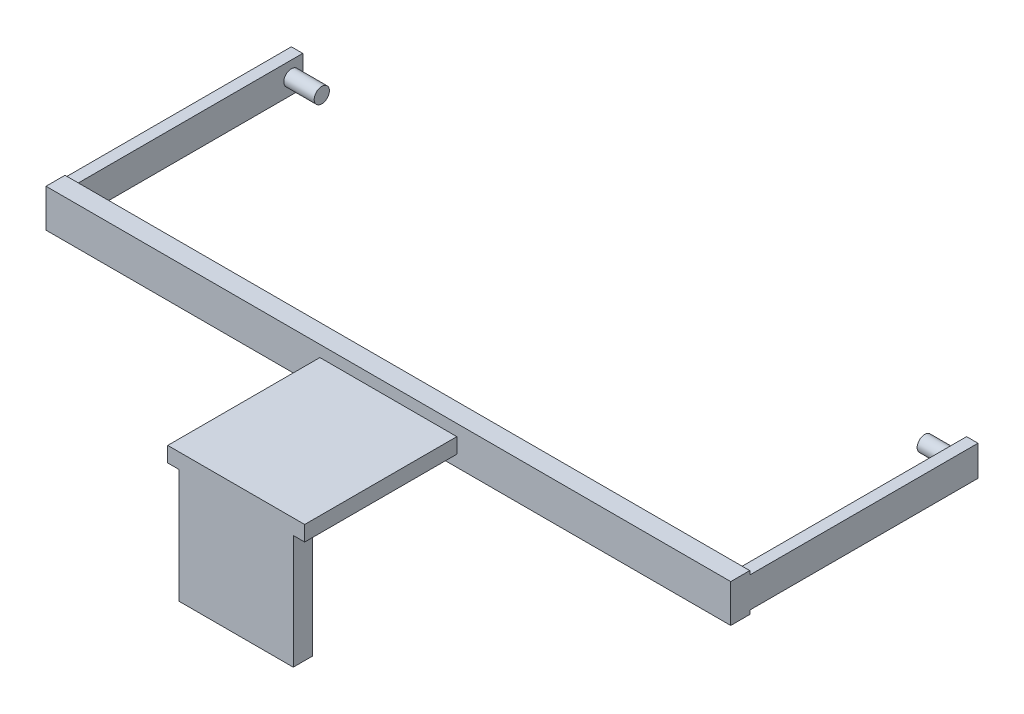
SolidWorks part; units mm, degrees
ref_plane "前视基准面" through (0, 0, 0) normal (0, 0, 1) x (1, 0, 0)
ref_plane "上视基准面" through (0, 0, 0) normal (0, 1, 0) x (1, 0, 0)
ref_plane "右视基准面" through (0, 0, 0) normal (1, 0, 0) x (0, 0, -1)
sketch "草图1" plane through (0, 0, 0) normal (0, 1, 0) x (1, 0, 0)
  line L1 (-90, 2.5) -> (90, 2.5)
  line L2 (-90, 2.5) -> (-90, -2.5)
  line L3 (-90, -2.5) -> (90, -2.5)
  line L4 (90, 2.5) -> (90, -2.5)
  line L5 (-90, 2.5) -> (90, -2.5) construction
  line L6 (-90, -2.5) -> (90, 2.5) construction
  point P0 (0, 0)
  dimension "D1" = 90
  dimension "D2" = 5
extrude "凸台-拉伸1" add sketch "草图1" along normal blind 10
sketch "草图2" plane through (0, 0, -2.5) normal (0, 0, -1) x (-1, 0, 0)
  line L0 (-90, 10) -> (-90, 0) construction
  line L1 (-90, 1) -> (-87, 1)
  line L2 (-90, 1) -> (-90, 9)
  line L3 (-90, 9) -> (-87, 9)
  line L4 (-87, 1) -> (-87, 9)
  line L5 (-90, 1) -> (-87, 9) construction
  line L6 (-90, 9) -> (-87, 1) construction
  line L7 (90, 10) -> (-90, 10) construction
  point P0 (-88.5, 5)
  point P7 (-88.5, 9)
  dimension "D1" = 3
  dimension "D2" = 0
  dimension "D3" = 8
  dimension "D4" = 1
extrude "凸台-拉伸2" add sketch "草图2" along normal blind 60
sketch "草图5" plane through (87, 0, 0) normal (-1, 0, 0) x (0, 0, 1)
  line L0 (-62.5, 9) -> (-2.5, 9) construction
  line L1 (-62.5, 1) -> (-62.5, 9) construction
  circle A0 centre (-59.5, 5) radius 2
  dimension "D1" = 4
  dimension "D2" = 4
  dimension "D3" = 3
extrude "凸台-拉伸4" add sketch "草图5" along normal blind 8
sketch "草图6" plane through (0, 0, 2.5) normal (0, 0, 1) x (1, 0, 0)
  line L0 (-90, 0) -> (90, 0) construction
  line L1 (-18, 7) -> (18, 7)
  line L2 (-18, 7) -> (-18, 3)
  line L3 (-18, 3) -> (18, 3)
  line L4 (18, 7) -> (18, 3)
  line L5 (-18, 7) -> (18, 3) construction
  line L6 (-18, 3) -> (18, 7) construction
  line L7 (90, 10) -> (90, 0) construction
  point P0 (0, 5)
  dimension "D1" = 5
  dimension "D2" = 90
  dimension "D3" = 4
  dimension "D4" = 36
extrude "凸台-拉伸5" add sketch "草图6" along normal blind 40
sketch "草图7" plane through (0, 3, 0) normal (0, -1, 0) x (1, 0, 0)
  line L0 (-18, 42.5) -> (18, 42.5) construction
  line L1 (15, 37.5) -> (-15, 37.5)
  line L2 (15, 37.5) -> (15, 42.5)
  line L3 (15, 42.5) -> (-15, 42.5)
  line L4 (-15, 37.5) -> (-15, 42.5)
  line L5 (15, 37.5) -> (-15, 42.5) construction
  line L6 (15, 42.5) -> (-15, 37.5) construction
  point P0 (0, 40)
  dimension "D1" = 5
  dimension "D2" = 30
extrude "凸台-拉伸6" add sketch "草图7" along normal blind 30
pattern_linear "阵列(线性)1" count 2 spacing 177.5 along (-1, 0, 0) of "凸台-拉伸2"
sketch "草图8" plane through (-87.5, 0, 0) normal (1, 0, 0) x (0, 0, -1)
  line L0 (62.5, 9) -> (62.5, 1) construction
  circle A0 centre (59.5, 5) radius 2
  dimension "D1" = 4
  dimension "D2" = 3
extrude "凸台-拉伸7" add sketch "草图8" along normal blind 8
